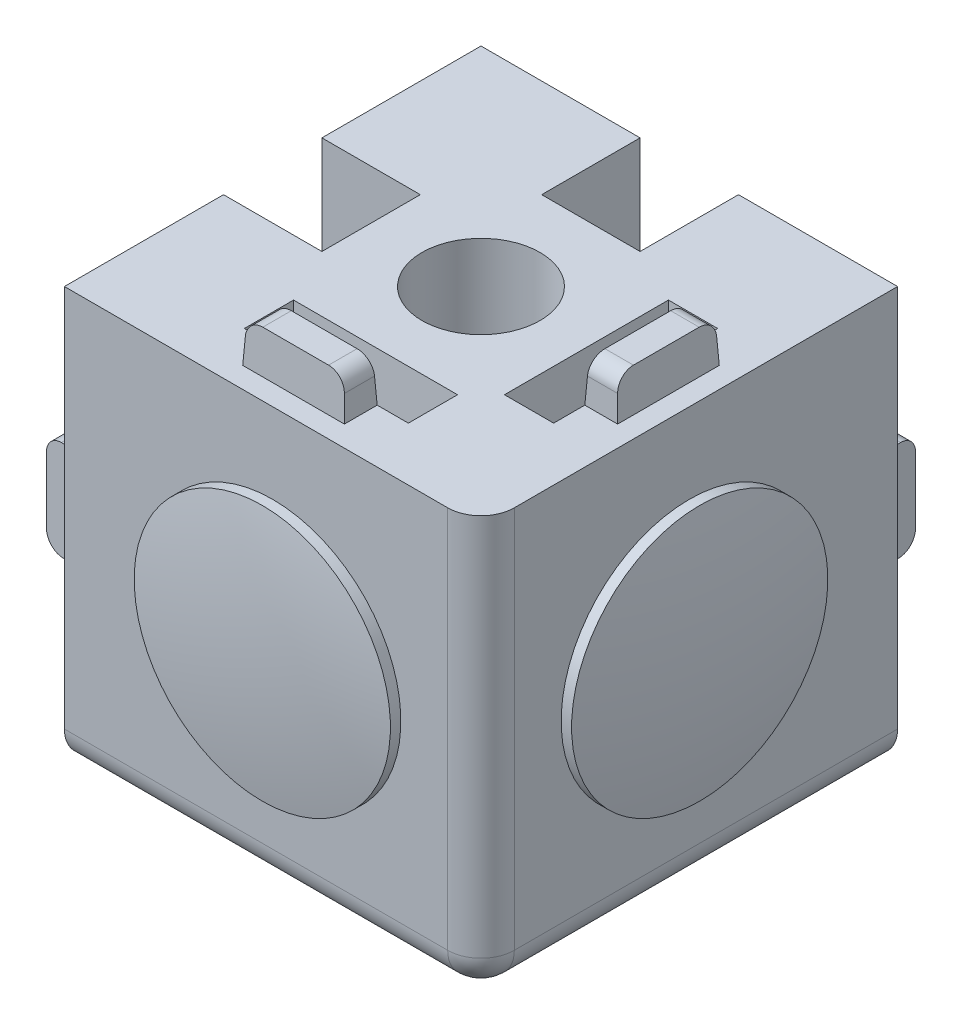
SolidWorks part; units mm, degrees
ref_plane "Front Plane" through (0, 0, 0) normal (0, 0, 1) x (1, 0, 0)
ref_plane "Top Plane" through (0, 0, 0) normal (0, 1, 0) x (1, 0, 0)
ref_plane "Right Plane" through (0, 0, 0) normal (1, 0, 0) x (0, 0, -1)
sketch "Sketch1" plane through (0, 0, 0) normal (0, 0, 1) x (1, 0, 0)
  line L0 (-12.7, -12.7) -> (12.7, 12.7) construction
  line L1 (-12.7, 12.7) -> (12.7, 12.7)
  line L2 (-12.7, 12.7) -> (-12.7, -12.7)
  line L3 (-12.7, -12.7) -> (12.7, -12.7)
  line L4 (12.7, 12.7) -> (12.7, -12.7)
  dimension "D1" = 25.4
extrude "Extrude1" add sketch "Sketch1" along normal mid plane 25.4
sketch "Sketch2" plane through (0, 0, 12.7) normal (0, 0, 1) x (1, 0, 0)
  circle A0 centre (0, 0) radius 6
  dimension "D1" = 12
extrude "Cut-Extrude1" cut sketch "Sketch2" against normal through all
sketch "Sketch3" plane through (0, 0, 12.7) normal (0, 0, 1) x (1, 0, 0)
  circle A0 centre (0, 0) radius 7.05
  dimension "D1" = 14.1
extrude "Cut-Extrude2" cut sketch "Sketch3" against normal through all draft 45
sketch "Sketch4" plane through (0, 0, -12.7) normal (0, 0, -1) x (-1, 0, 0)
  circle A0 centre (0, 0) radius 3.6
  circle A1 centre (0, 0) radius 6 construction
  circle A2 centre (0, 0) radius 6
  dimension "D1" = 7.2
extrude "Extrude2" add sketch "Sketch4" against normal blind 6
sketch "Sketch5" plane through (0, 0, 0) normal (1, 0, 0) x (0, 0, -1)
  line L1 (6.7, 12.7) -> (12.7, 12.7)
  line L2 (6.7, 12.7) -> (6.7, 6.7)
  line L3 (6.7, 6.7) -> (12.7, 6.7)
  line L4 (12.7, 12.7) -> (12.7, 6.7)
  dimension "D1" = 6
extrude "Cut-Extrude3" cut sketch "Sketch5" against normal mid plane 6
sketch "Sketch6" plane through (0, 0, -12.7) normal (0, 0, -1) x (-1, 0, 0)
  line L0 (0, 0) -> (9.43, 0) construction
  line L1 (-11.43, 3.1) -> (-9.43, 3.1)
  line L2 (-11.43, 3.1) -> (-11.43, -3.1)
  line L3 (-11.43, -3.1) -> (-9.43, -3.1)
  line L4 (-9.43, 3.1) -> (-9.43, -3.1)
  line L5 (9.43, 3.1) -> (11.43, 3.1) construction
  line L6 (9.43, 3.1) -> (9.43, -3.1) construction
  line L7 (9.43, -3.1) -> (11.43, -3.1) construction
  line L8 (11.43, 3.1) -> (11.43, -3.1) construction
  line L9 (-3.1, -9.43) -> (3.1, -9.43)
  line L10 (-3.1, -9.43) -> (-3.1, -11.43)
  line L11 (-3.1, -11.43) -> (3.1, -11.43)
  line L12 (3.1, -9.43) -> (3.1, -11.43)
  line L13 (0, 0) -> (0, -9.43) construction
  line L14 (-12.7, -12.7) -> (-12.7, 12.7) construction
  line L15 (12.7, 12.7) -> (12.7, -12.7) construction
  line L16 (12.7, -12.7) -> (-12.7, -12.7) construction
  dimension "D1" = 1.27
  dimension "D2" = 6.2
  dimension "D3" = 2
  dimension "D4" = 1.27
  dimension "D5" = 1.27
extrude "Extrude3" add sketch "Sketch6" along normal blind 2.5 draft 3
fillet "Fillet1" radius 1.016 4 edges at (10.43, -2.969, -15.2) (10.43, 2.969, -15.2) (2.969, -10.43, -15.2) (-2.969, -10.43, -15.2)
sketch "Sketch7" plane through (0, 0, 0) normal (0, 1, 0) x (1, 0, 0)
  line L0 (0, 0) -> (-12.7, 0) construction
  line L1 (-12.7, -12.7) -> (-12.7, 12.7) construction
ref_axis "Axis1" through (-12.7, 0, 0) along (1, 0, 0)
sketch "Sketch9" plane through (0, 0, 0) normal (0, 0, 1) x (1, 0, 0)
  line L0 (0, 0) -> (0, 11.5939) construction
  point P3 (3.5103, -3.0266)
ref_axis "Axis2" through (0, 11.5939, 0) along (0, -1, 0)
sketch "Sketch8" plane through (0, 0, -12.7) normal (0, 0, -1) x (-1, 0, 0)
  line L0 (3.1, -9.43) -> (-3.1, -9.43) construction
  line L1 (-9.43, 5) -> (-6.43, 5)
  line L2 (-9.43, 5) -> (-9.43, -5)
  line L3 (-9.43, -5) -> (-6.43, -5)
  line L4 (-6.43, 5) -> (-6.43, -5)
  line L5 (-5, -6.43) -> (5, -6.43)
  line L6 (-5, -6.43) -> (-5, -9.43)
  line L7 (-5, -9.43) -> (5, -9.43)
  line L8 (5, -6.43) -> (5, -9.43)
  line L13 (-9.43, -3.1) -> (-9.43, 3.1) construction
  line L15 (0, 0) -> (0, -6.43) construction
  line L16 (0, 0) -> (-6.43, 0) construction
  dimension "D1" = 3
  dimension "D2" = 10
extrude "Cut-Extrude4" cut sketch "Sketch8" against normal blind 5 draft 3
pattern_circular "CirPattern1" count 2 over 90 about axis through (-12.7, 0, 0) along (1, 0, 0) of "Cut-Extrude1", "Cut-Extrude2", "Extrude2"
pattern_circular "CirPattern2" count 2 over 90 about axis through (0, 11.5939, 0) along (0, -1, 0) of "Cut-Extrude1", "Cut-Extrude2", "Extrude2"
ref_plane "Plane1" through (0, 0, 0) normal (0, 0.7071, 0.7071) x (1, 0, 0)
mirror "Mirror1" about plane through (0, 0, 0) normal (0, 0.7071, 0.7071) of "Cut-Extrude4", "Fillet1", "Extrude3"
ref_plane "Plane2" through (0, 0, 0) normal (0.7071, 0, -0.7071) x (-0.7071, 0, -0.7071)
mirror "Mirror2" about plane through (0, 0, 0) normal (0.7071, 0, -0.7071) of "Cut-Extrude3", "Cut-Extrude4", "Fillet1", "Extrude3"
sketch "Sketch10" plane through (0, 0, 0) normal (0, 1, 0) x (1, 0, 0)
  line L0 (-3, 12.7) -> (3, 12.7) construction
  line L1 (-12.7, 12.7) -> (-6.7, 12.7)
  line L2 (-12.7, 12.7) -> (-12.7, 6.7)
  line L3 (-12.7, 6.7) -> (-6.7, 6.7)
  line L4 (-6.7, 12.7) -> (-6.7, 6.7)
extrude "Cut-Extrude5" cut sketch "Sketch10" against normal mid plane 6
fillet "Fillet2" radius 2.032 3 edges at (0, -12.7, 12.7) (12.7, -12.7, 0) (12.7, 0, 12.7)
sketch "Sketch11" plane through (0, 0, 0) normal (1, 0, 0) x (0, 0, -1)
  line L0 (-13.335, 7.812) -> (-12.7, 7.812)
  line L1 (-12.7, 7.812) -> (-12.7, 5.9746)
  line L2 (-12.7, 5.9746) -> (-8.1026, 5.9746)
  line L3 (-8.1026, 5.9746) -> (-8.1026, 4.7046)
  line L5 (-8.1026, 4.7046) -> (-12.065, 4.7046)
  line L6 (-12.065, 4.7046) -> (-12.065, 0)
  line L7 (-12.065, 0) -> (-13.97, 0)
  line L8 (-13.335, 7.812) -> (-13.335, 0) construction
  line L9 (-11.65, 6) -> (-11.65, -6) construction
  line L10 (-12.7, 7.05) -> (-12.7, -7.05) construction
  line L11 (-11.65, 6) -> (-11.65, -6) construction
  line L12 (-12.7, 7.05) -> (-12.7, -7.05) construction
  arc A0 (-13.97, 0) -> (-13.335, 7.812) centre (34.4005, 0) cw
  dimension "D1" = 0.635
  dimension "D2" = 0.635
  dimension "D3" = 1.27
  dimension "D4" = 3.9624
  dimension "D5" = 1.27
  dimension "D6" = 0.762
  dimension "D7" = 0.0254
revolve "Revolve1" add sketch "Sketch11" angle 360 about L7
mirror "Mirror3" about plane through (0, 0, 0) normal (0, 0.7071, 0.7071) of bodies 113
mirror "Mirror4" about plane through (0, 0, 0) normal (0.7071, 0, -0.7071) of bodies 113
equation "\"D1@Cut-Extrude5\" = \"D1@Cut-Extrude3\""
